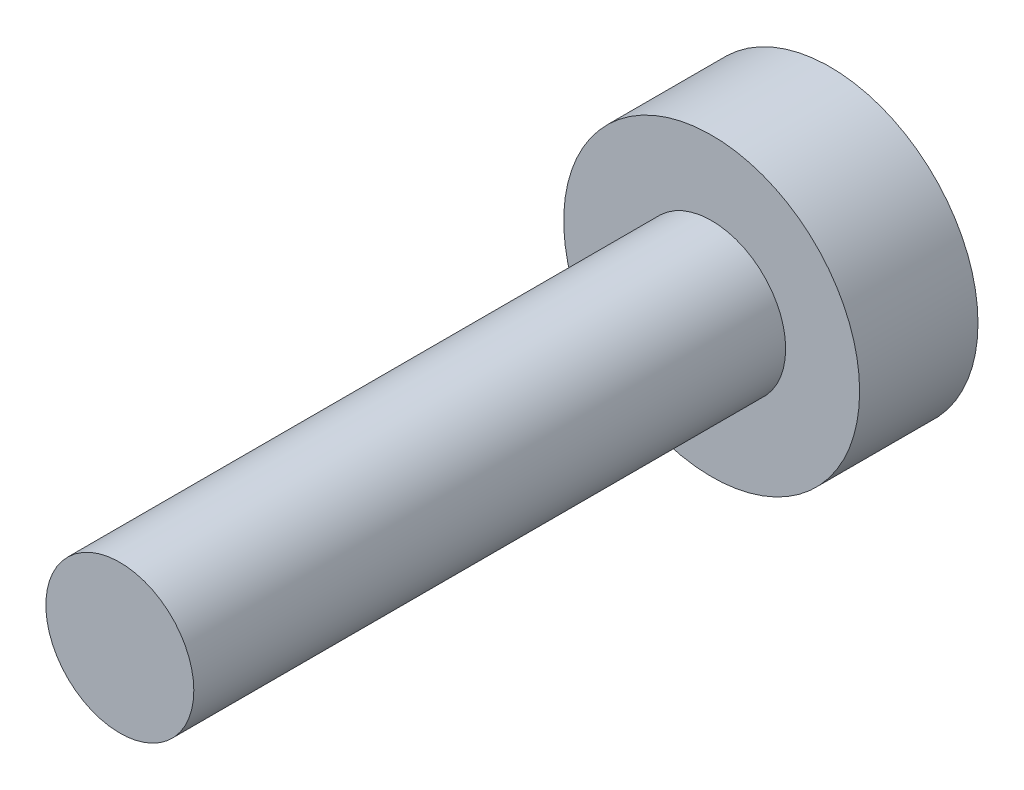
SolidWorks part; units mm, degrees
ref_plane "前视基准面" through (0, 0, 0) normal (0, 0, 1) x (1, 0, 0)
ref_plane "上视基准面" through (0, 0, 0) normal (0, 1, 0) x (1, 0, 0)
ref_plane "右视基准面" through (0, 0, 0) normal (1, 0, 0) x (0, 0, -1)
sketch "草图1" plane through (0, 0, 0) normal (0, 0, 1) x (1, 0, 0)
  circle A0 centre (0, 0) radius 1.25
  dimension "D1" = 2.5
extrude "公称杆长10_无牙型参考" add sketch "草图1" along normal blind 10
sketch "草图2" plane through (0, 0, 0) normal (0, 0, 1) x (1, 0, 0)
  circle A0 centre (0, 0) radius 2.5
  dimension "D1" = 5
extrude "螺丝头_端面为长度基准" add sketch "草图2" along normal blind 2 from offset 2
